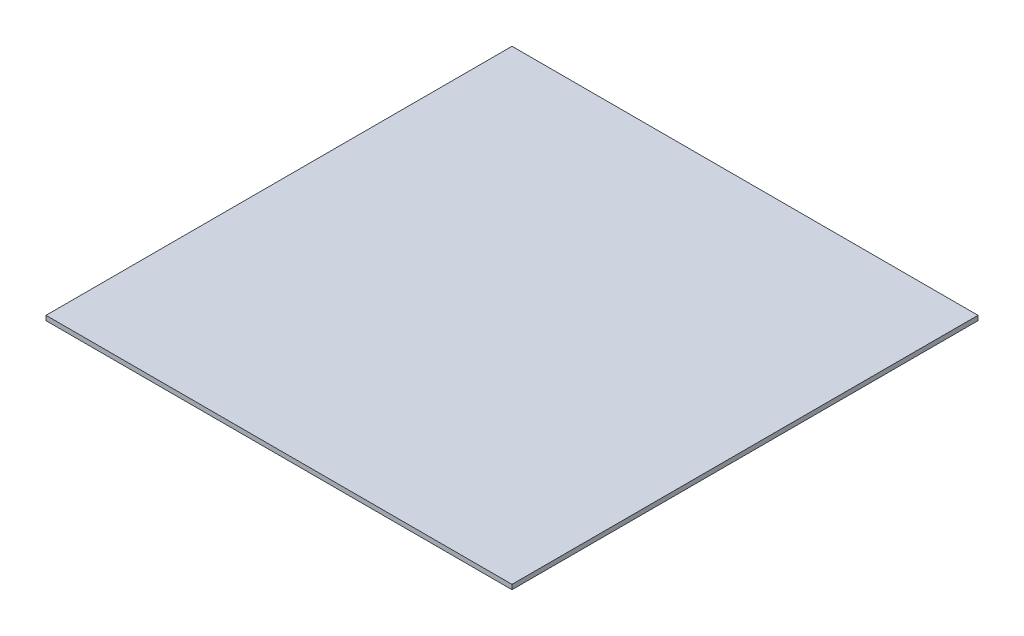
SolidWorks part; units mm, degrees
ref_plane "Front Plane" through (0, 0, 0) normal (0, 0, 1) x (1, 0, 0)
ref_plane "Top Plane" through (0, 0, 0) normal (0, 1, 0) x (1, 0, 0)
ref_plane "Right Plane" through (0, 0, 0) normal (1, 0, 0) x (0, 0, -1)
sketch "Sketch1" plane through (0, 0, 0) normal (0, 1, 0) x (1, 0, 0)
  line L1 (-1000, -1000) -> (1000, -1000)
  line L2 (-1000, -1000) -> (-1000, 1000)
  line L3 (-1000, 1000) -> (1000, 1000)
  line L4 (1000, -1000) -> (1000, 1000)
  line L5 (-1000, -1000) -> (1000, 1000) construction
  line L6 (-1000, 1000) -> (1000, -1000) construction
  point P0 (0, 0)
  dimension "D1" = 2000
  dimension "D2" = 2000
extrude "Boss-Extrude1" add sketch "Sketch1" along normal blind 20
